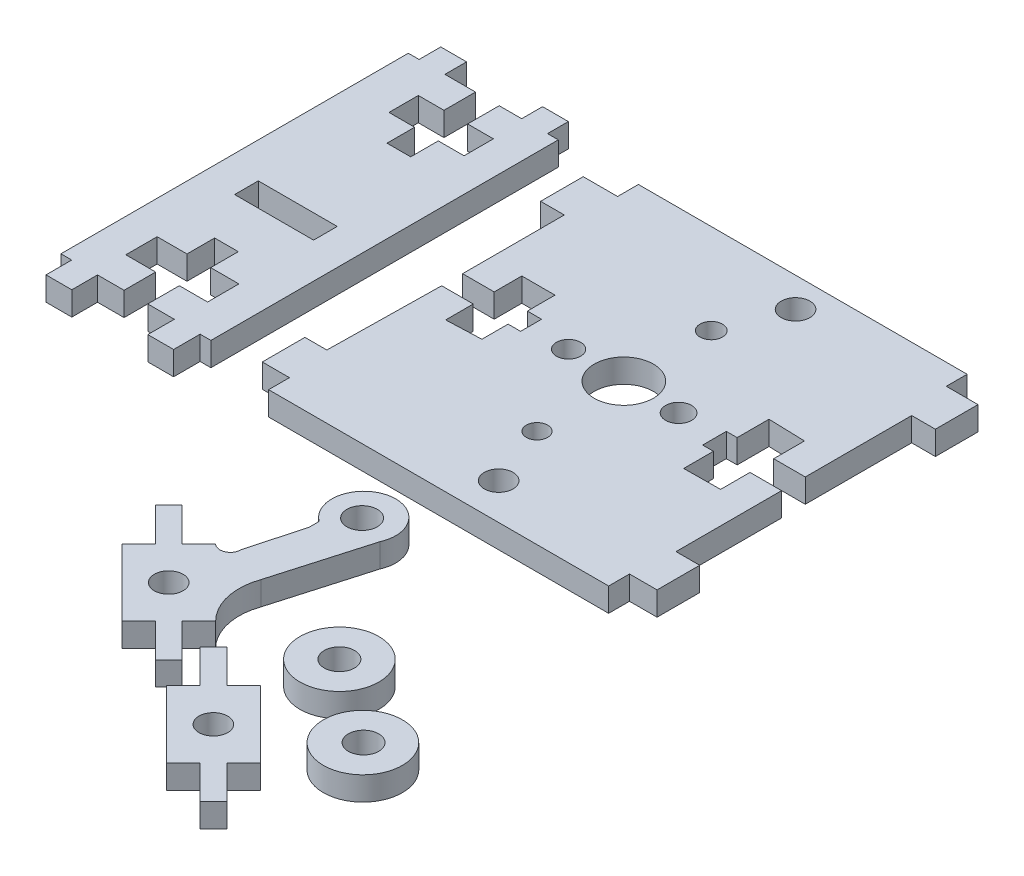
SolidWorks part; units mm, degrees
ref_plane "Front Plane" through (0, 0, 0) normal (0, 0, 1) x (1, 0, 0)
ref_plane "Top Plane" through (0, 0, 0) normal (0, 1, 0) x (1, 0, 0)
ref_plane "Right Plane" through (0, 0, 0) normal (1, 0, 0) x (0, 0, -1)
sketch "Sketch6" plane through (0, 0, -6.8736) normal (0, 1, 0) x (1, 0, 0)
  line L2 (242.3822, 6.9177) -> (239.3822, 6.9177)
  line L3 (239.3822, 6.9177) -> (239.3822, -6.559)
  line L4 (239.3822, -6.559) -> (235.3822, -6.559)
  line L5 (235.3822, -6.559) -> (235.3822, -2.6617)
  line L6 (235.3822, -2.6617) -> (230.7498, -2.5211)
  line L7 (230.7498, -2.5211) -> (230.7498, -6.559)
  line L8 (230.7498, -6.559) -> (229.3822, -6.559)
  line L9 (229.3822, -6.559) -> (229.3822, -9.559)
  line L10 (229.3822, -9.559) -> (230.7487, -9.559)
  line L11 (230.7487, -9.559) -> (230.7487, -13.3299)
  line L12 (230.7487, -13.3299) -> (235.3822, -13.2836)
  line L13 (235.3822, -13.2836) -> (235.3822, -9.559)
  line L14 (235.3822, -9.559) -> (239.3822, -9.559)
  line L15 (239.3822, -9.559) -> (239.3822, -22.9319)
  line L16 (239.3822, -22.9319) -> (242.3822, -22.9319)
  line L20 (192.3822, -22.9319) -> (195.1572, -22.9319)
  line L21 (195.3822, -8.6127) -> (199.3822, -8.6127)
  line L22 (199.3822, -8.6127) -> (199.3822, -12.1092)
  line L23 (199.3822, -12.1092) -> (203.7977, -11.9311)
  line L24 (203.7977, -11.9311) -> (203.7977, -8.6127)
  line L25 (203.7977, -8.6127) -> (205.3822, -8.6127)
  line L26 (205.3822, -8.6127) -> (205.3822, -5.9615)
  line L27 (205.3822, -5.9615) -> (203.5871, -5.9615)
  line L28 (203.5871, -5.9615) -> (203.5871, -2.4623)
  line L29 (203.5871, -2.4623) -> (199.3822, -2.4623)
  line L30 (199.3822, -2.4623) -> (199.3822, -5.9615)
  line L31 (199.3822, -5.9615) -> (195.3822, -5.9615)
  line L32 (195.3822, -5.9615) -> (195.3822, 6.9177)
  line L33 (195.3822, 6.9177) -> (192.3822, 6.9177)
  line L35 (195.1572, -22.9319) -> (195.3822, -8.6127)
  line L36 (172.3993, 17.524) -> (172.3993, 14.7799)
  line L37 (172.3993, 14.7799) -> (176.2794, 14.7799)
  line L38 (176.2794, 14.7799) -> (176.2794, 10.7799)
  line L39 (176.2794, 10.7799) -> (173.032, 10.7799)
  line L40 (173.032, 10.7799) -> (173.032, 7.063)
  line L41 (173.032, 7.063) -> (176.2794, 7.063)
  line L42 (176.2794, 7.063) -> (176.2794, 3.563)
  line L43 (176.2794, 3.563) -> (179.2794, 3.563)
  line L44 (179.2794, 3.563) -> (179.2794, 7.063)
  line L45 (179.2794, 7.063) -> (182.5439, 7.063)
  line L46 (182.5439, 7.063) -> (182.5439, 10.7799)
  line L47 (182.5439, 10.7799) -> (179.2794, 10.7799)
  line L48 (179.2794, 10.7799) -> (179.2794, 14.7799)
  line L49 (179.2794, 14.7799) -> (182.1277, 14.7799)
  line L50 (182.1277, 14.7799) -> (182.1277, 17.4216)
  line L54 (182.1277, -32.5784) -> (182.1277, -29.2201)
  line L55 (182.1277, -29.2201) -> (178.7635, -29.2201)
  line L56 (178.7635, -29.2201) -> (178.7635, -25.2201)
  line L57 (178.7635, -25.2201) -> (182.3404, -25.2201)
  line L58 (182.3404, -25.2201) -> (182.3404, -21.2526)
  line L59 (182.3404, -21.2526) -> (178.7635, -21.2526)
  line L60 (178.7635, -21.2526) -> (178.7635, -17.7526)
  line L61 (178.7635, -17.7526) -> (175.7635, -17.7526)
  line L62 (175.7635, -17.7526) -> (175.7635, -21.2526)
  line L63 (175.7635, -21.2526) -> (171.9828, -21.2526)
  line L64 (171.9828, -21.2526) -> (171.9828, -25.2201)
  line L65 (171.9828, -25.2201) -> (175.7635, -25.2201)
  line L66 (175.7635, -25.2201) -> (175.7635, -29.2201)
  line L67 (175.7635, -29.2201) -> (172.3993, -29.2201)
  line L68 (172.3993, -29.2201) -> (172.3993, -32.476)
  line L72 (172.2635, -8.7201) -> (182.2635, -8.7201)
  line L73 (182.2635, -8.7201) -> (182.2635, -11.7201)
  line L74 (182.2635, -11.7201) -> (172.2635, -11.7201)
  line L75 (172.2635, -11.7201) -> (172.2635, -8.7201)
  line L84 (217.8601, -59.7241) -> (215.7388, -61.8454)
  line L85 (215.7388, -61.8454) -> (219.9814, -66.0881)
  line L86 (219.9814, -66.0881) -> (218.2844, -67.7851)
  line L87 (218.2844, -67.7851) -> (214.0417, -63.5425)
  line L88 (214.0417, -63.5425) -> (211.9204, -65.6638)
  line L89 (211.9204, -65.6638) -> (203.4351, -57.1785)
  line L90 (203.4351, -57.1785) -> (205.5564, -55.0572)
  line L91 (205.5564, -55.0572) -> (201.3138, -50.8146)
  line L92 (201.3138, -50.8146) -> (203.0109, -49.1175)
  line L93 (203.0109, -49.1175) -> (207.2535, -53.3602)
  line L94 (207.2535, -53.3602) -> (209.3748, -51.2388)
  line L95 (211.633, -50.3035) -> (213.4745, -43.4567)
  line L96 (216.1631, -52.2995) -> (219.5483, -40.5807)
  line L97 (213.4745, -43.4567) -> (213.4745, -42.2199)
  line L98 (227.7596, -63.9668) -> (236.245, -72.452)
  line L99 (236.245, -72.452) -> (234.1237, -74.5733)
  line L100 (234.1237, -74.5733) -> (238.3663, -78.816)
  line L101 (238.3663, -78.816) -> (236.6692, -80.513)
  line L102 (236.6692, -80.513) -> (232.4266, -76.2704)
  line L103 (232.4266, -76.2704) -> (230.3053, -78.3917)
  line L104 (230.3053, -78.3917) -> (221.8199, -69.9065)
  line L105 (221.8199, -69.9065) -> (223.9412, -67.7851)
  line L106 (223.9412, -67.7851) -> (219.6986, -63.5425)
  line L107 (219.6986, -63.5425) -> (221.3956, -61.8454)
  line L108 (221.3956, -61.8454) -> (225.6383, -66.0881)
  line L109 (225.6383, -66.0881) -> (227.7596, -63.9668)
  line L118 (242.3822, -28.3319) -> (238.8902, -28.3319)
  line L119 (238.8902, -28.3319) -> (238.8902, -30.9716)
  line L120 (192.3822, -28.3319) -> (195.8238, -28.3319)
  line L121 (195.8238, -28.3319) -> (195.8238, -30.9716)
  line L122 (242.3822, -28.3319) -> (242.3822, -22.9319)
  line L123 (238.8902, -30.9716) -> (195.8238, -30.9716)
  line L124 (192.3822, -28.3319) -> (192.3822, -22.9319)
  line L125 (238.3663, 14.9574) -> (238.3663, 12.3177)
  line L126 (238.3663, 12.3177) -> (242.3822, 12.3177)
  line L127 (192.3822, 12.3177) -> (196.7311, 12.3177)
  line L128 (196.7311, 12.3177) -> (196.7311, 14.9574)
  line L129 (196.7311, 14.9574) -> (238.3663, 14.9574)
  line L130 (192.3822, 12.3177) -> (192.3822, 6.9177)
  line L131 (242.3822, 6.9177) -> (242.3822, 12.3177)
  line L132 (186.7635, -29.2201) -> (185.3957, -29.2201)
  line L133 (185.3957, -29.2201) -> (185.3957, -32.5784)
  line L134 (167.7635, -29.2201) -> (169.1313, -29.2201)
  line L135 (169.1313, -29.2201) -> (169.1313, -32.476)
  line L136 (169.1313, 17.524) -> (169.1313, 14.7799)
  line L137 (169.1313, 14.7799) -> (167.7635, 14.7799)
  line L138 (185.3957, 17.4216) -> (185.3957, 14.7799)
  line L139 (185.3957, 14.7799) -> (186.7635, 14.7799)
  line L140 (167.7635, 14.7799) -> (167.7635, -29.2201)
  line L141 (169.1313, -32.476) -> (172.3993, -32.476)
  line L142 (182.1277, 17.4216) -> (185.3957, 17.4216)
  line L143 (186.7635, 14.7799) -> (186.7635, -29.2201)
  line L144 (185.3957, -32.5784) -> (182.1277, -32.5784)
  line L145 (169.1313, 17.524) -> (172.3993, 17.524)
  circle A0 centre (217.3822, -7.5426) radius 3.75
  circle A1 centre (210.3822, -7.5426) radius 1.5333
  circle A2 centre (217.3726, 3.5398) radius 1.4239
  circle A3 centre (224.3329, -7.5545) radius 1.6482
  circle A4 centre (220.3822, 11.2074) radius 1.82
  circle A5 centre (217.3822, -18.5367) radius 1.3524
  circle A6 centre (220.3686, -26.382) radius 1.82
  arc A13 (209.3748, -51.2388) -> (211.633, -50.3035) centre (210.3102, -50.3035) ccw
  arc A14 (217.8601, -59.7241) -> (216.1631, -52.2995) centre (222.9237, -54.6605) cw
  circle A15 centre (215.824, -39.1328) radius 1.925
  arc A16 (219.5483, -40.5807) -> (213.4745, -42.2199) centre (215.8488, -38.9451) ccw
  circle A17 centre (210.6476, -58.4513) radius 1.8201
  circle A18 centre (229.8748, -56.0569) radius 1.925
  circle A19 centre (229.8748, -56.0569) radius 5
  circle A20 centre (240.5423, -63.668) radius 1.925
  circle A21 centre (240.5012, -63.7091) radius 5.004
  circle A22 centre (229.0324, -71.1792) radius 1.82
  dimension "D2" = 3.85
  dimension "D1" = 3.6402
  dimension "D3" = 3.64
  dimension "D4" = 3.85
  dimension "D5" = 3.85
  dimension "D13" = 3.64
  dimension "D14" = 3.64
  dimension "D6" = 1.3678
  dimension "D7" = 3.268
  dimension "D8" = 5.4
  dimension "D9" = 5.4
  dimension "D10" = 5.4
  dimension "D11" = 5.4
  dimension "D12" = 2.6397
extrude "Boss-Extrude1" add sketch "Sketch6" along normal blind 3
